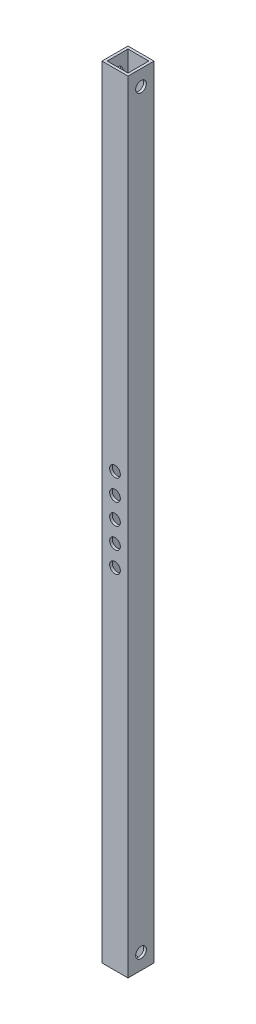
SolidWorks part; units mm, degrees
material "1345 Alloy"
ref_plane "Front Plane" through (0, 0, 0) normal (0, 0, 1) x (1, 0, 0)
ref_plane "Top Plane" through (0, 0, 0) normal (0, 1, 0) x (1, 0, 0)
ref_plane "Right Plane" through (0, 0, 0) normal (1, 0, 0) x (0, 0, -1)
sketch "Sketch1" plane through (0, 0, 0) normal (0, 1, 0) x (1, 0, 0)
  line L1 (-5, 5) -> (5, 5)
  line L2 (-5, 5) -> (-5, -5)
  line L3 (-5, -5) -> (5, -5)
  line L4 (5, 5) -> (5, -5)
  line L5 (-5, 5) -> (5, -5) construction
  line L6 (-5, -5) -> (5, 5) construction
  line L7 (-4, 4) -> (4, 4)
  line L8 (-4, 4) -> (-4, -4)
  line L9 (-4, -4) -> (4, -4)
  line L10 (4, 4) -> (4, -4)
  line L11 (-4, 4) -> (4, -4) construction
  line L12 (-4, -4) -> (4, 4) construction
  point P0 (0, 0)
  point P6 (0, 0)
  dimension "D1" = 10
  dimension "D2" = 10
  dimension "D3" = 8
  dimension "D4" = 8
extrude "Boss-Extrude1" add sketch "Sketch1" along normal blind 300
sketch "Sketch2" plane through (5, 0, 0) normal (1, 0, 0) x (0, 0, -1)
  line L0 (0, 234.1306) -> (0, -6.817) construction
  line L1 (-5, 300) -> (5, 300) construction
  line L2 (-5, 150) -> (18.888, 150) construction
  line L3 (-5, 300) -> (-5, 0) construction
  circle A0 centre (0, 294) radius 2.05
  circle A1 centre (0, 6) radius 2.05
  point P9 (-5, 115)
  point P12 (0, 0)
  dimension "D1" = 4.1
  dimension "D2" = 6
extrude "Cut-Extrude1" cut sketch "Sketch2" against normal through all
sketch "Sketch3" plane through (0, 0, 5) normal (0, 0, 1) x (1, 0, 0)
  line L0 (0, 234.5439) -> (0, -8.0568) construction
  line L1 (-5, 150) -> (18.3914, 150) construction
  line L2 (-5, 300) -> (-5, 0) construction
  circle A0 centre (0, 150) radius 2.05
  circle A1 centre (0, 158) radius 2.05
  circle A2 centre (0, 166) radius 2.05
  circle A3 centre (0, 142) radius 2.05
  circle A4 centre (0, 134) radius 2.05
  dimension "D1" = 4.1
  dimension "D3" = 16
  dimension "D5" = 16
  dimension "D2" = 3
  dimension "D4" = 3
extrude "Cut-Extrude2" cut sketch "Sketch3" against normal through all
